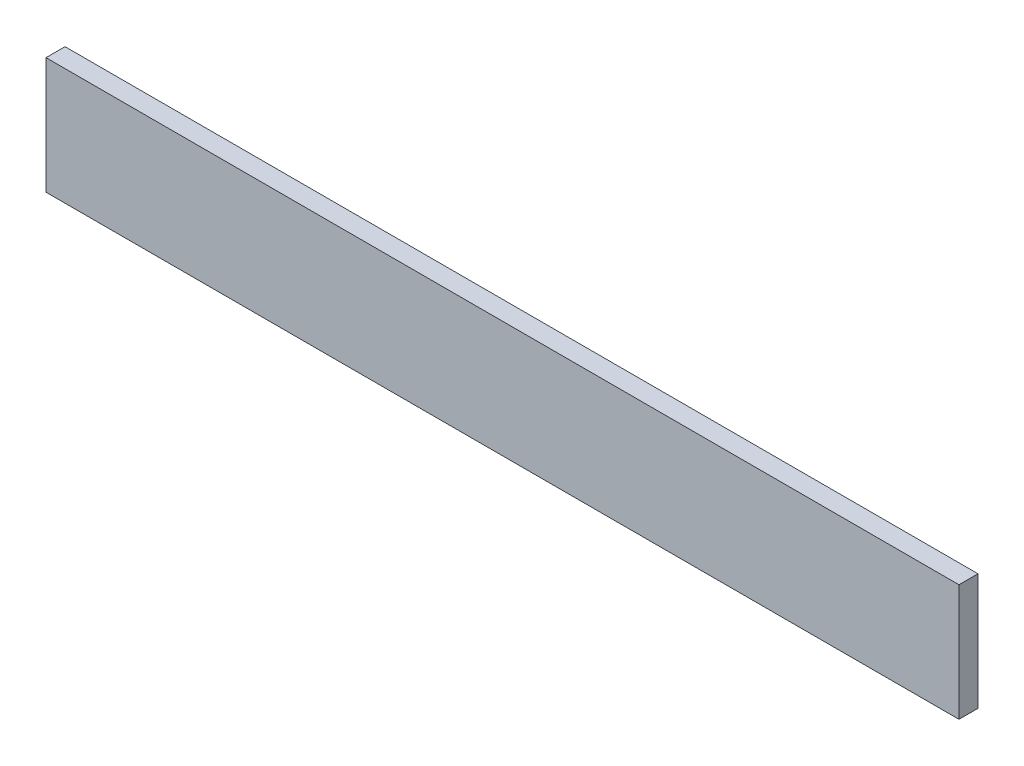
SolidWorks part; units mm, degrees
ref_plane "Front Plane" through (0, 0, 0) normal (0, 0, 1) x (1, 0, 0)
ref_plane "Top Plane" through (0, 0, 0) normal (0, 1, 0) x (1, 0, 0)
ref_plane "Right Plane" through (0, 0, 0) normal (1, 0, 0) x (0, 0, -1)
sketch "Sketch1" plane through (0, 0, 0) normal (0, 0, 1) x (1, 0, 0)
  line L1 (-124.4206, 35.9397) -> (789.9794, 35.9397)
  line L2 (-124.4206, 35.9397) -> (-124.4206, -80.8036)
  line L3 (-124.4206, -80.8036) -> (789.9794, -80.8036)
  line L4 (789.9794, 35.9397) -> (789.9794, -80.8036)
  line L5 (-124.4206, 35.9397) -> (789.9794, -80.8036) construction
  line L6 (-124.4206, -80.8036) -> (789.9794, 35.9397) construction
  point P0 (332.7794, -22.432)
extrude "Boss-Extrude1" add sketch "Sketch1" along normal blind 19.05 contours L2 L1 L4 L3
